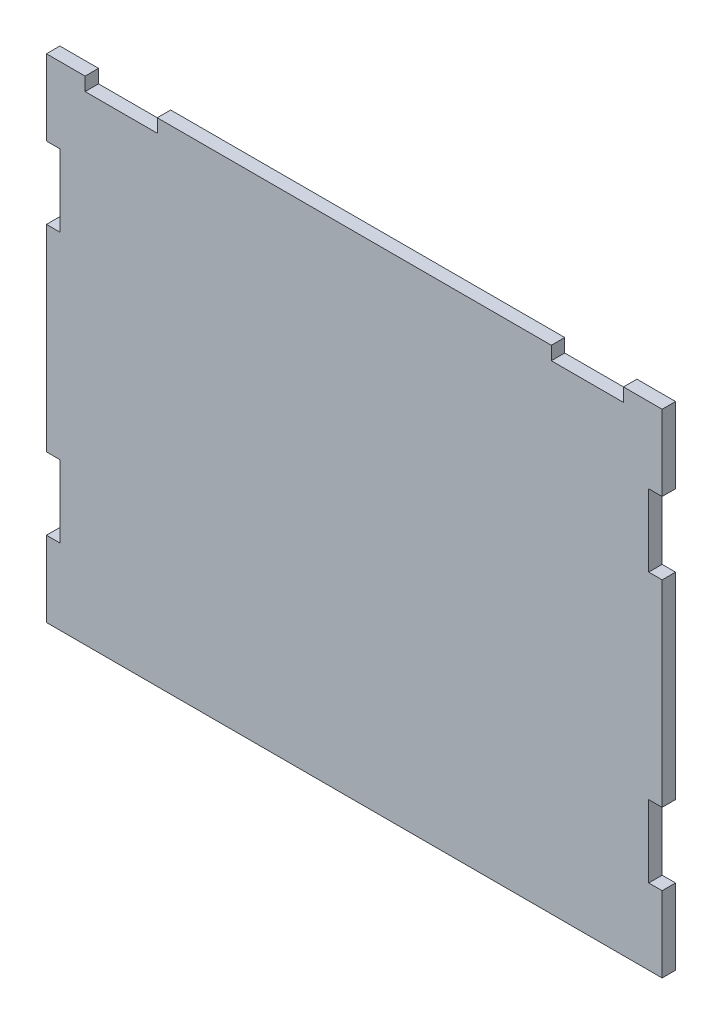
SolidWorks part; units mm, degrees
ref_plane "Спереди" through (0, 0, 0) normal (0, 0, 1) x (1, 0, 0)
ref_plane "Сверху" through (0, 0, 0) normal (0, 1, 0) x (1, 0, 0)
ref_plane "Справа" through (0, 0, 0) normal (1, 0, 0) x (0, 0, -1)
other "Configuration Table"
sketch "Эскиз1" plane through (0, 0, 0) normal (0, 0, 1) x (1, 0, 0)
  line L0 (-234.3, 0) -> (-250, 0)
  line L16 (0, 0) -> (-15.7, 0)
  line L25 (0, 0) -> (0, -30.7)
  line L26 (0, -200) -> (-250, -200)
  line L32 (-250, 0) -> (-250, -30.7)
  line L34 (-15.7, 0) -> (-15.7, -5.45)
  line L35 (-15.7, -5.45) -> (-45, -5.45)
  line L36 (-45, 0) -> (-45, -5.45)
  line L38 (-234.3, 0) -> (-234.3, -5.45)
  line L39 (-234.3, -5.45) -> (-205, -5.45)
  line L40 (-205, 0) -> (-205, -5.45)
  line L41 (-45, 0) -> (-205, 0)
  line L42 (-125, 0) -> (-125, -200) construction
  line L43 (0, -30.7) -> (-5.45, -30.7)
  line L45 (0, -60) -> (-5.45, -60)
  line L46 (-5.45, -30.7) -> (-5.45, -60)
  line L47 (0, -169.3) -> (-5.45, -169.3)
  line L49 (0, -140) -> (-5.45, -140)
  line L50 (-5.45, -169.3) -> (-5.45, -140)
  line L51 (0, -169.3) -> (0, -200)
  line L52 (0, -60) -> (0, -140)
  line L53 (-250, -169.3) -> (-244.55, -169.3)
  line L54 (-244.55, -169.3) -> (-244.55, -140)
  line L55 (-250, -140) -> (-244.55, -140)
  line L56 (-250, -60) -> (-244.55, -60)
  line L57 (-250, -30.7) -> (-244.55, -30.7)
  line L58 (-244.55, -30.7) -> (-244.55, -60)
  line L59 (-250, -60) -> (-250, -140)
  line L60 (-250, -169.3) -> (-250, -200)
  dimension "D2" = 200
  dimension "D3" = 250
  dimension "D4" = 29.3
  dimension "D5" = 5.45
  dimension "D6" = 29.3
  dimension "D7" = 15.7
  dimension "D8" = 5.45
  dimension "D9" = 29.3
  dimension "D10" = 5.45
  dimension "D11" = 30.7
  dimension "D12" = 29.3
  dimension "D13" = 30.7
  dimension "D14" = 5.45
extrude "Бобышка-Вытянуть1" add sketch "Эскиз1" along normal blind 5.45
